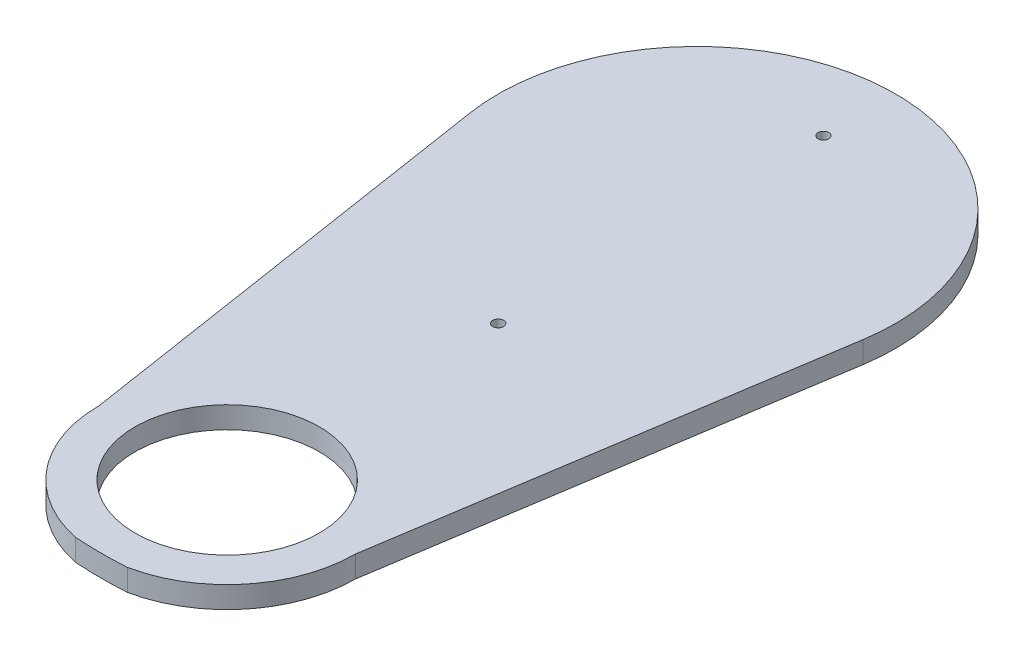
SolidWorks part; units mm, degrees
ref_plane "Front" through (0, 0, 0) normal (0, 0, 1) x (1, 0, 0)
ref_plane "Top" through (0, 0, 0) normal (0, 1, 0) x (1, 0, 0)
ref_plane "Right" through (0, 0, 0) normal (1, 0, 0) x (0, 0, -1)
sketch "Sketch1" plane through (0, 0, 0) normal (0, 1, 0) x (1, 0, 0)
  line L0 (110, 0) -> (-110, 0) construction
  line L1 (0, 0) -> (0, -110) construction
  line L2 (0, 0) -> (0, 110) construction
  line L3 (63.2456, 90) -> (-63.2456, 90)
  line L4 (80.4674, -75) -> (-80.4674, -75)
  circle A0 centre (0, 0) radius 110
  circle A1 centre (0, -75) radius 25.5
  circle A3 centre (0, 90) radius 1.5
  circle A4 centre (0, 0) radius 1.5
  point P6 (0, 0)
  point P16 (0, 90)
  point P19 (0, -75)
  dimension "D1" = 220
  dimension "D3" = 51
  dimension "D2" = 75
  dimension "D4" = 3
  dimension "D5" = 90
  dimension "D6" = 3
extrude "Boss-Extrude1" add sketch "Sketch1" along normal blind 6 contours A3 L3 A0 L4 A1 A4 | A1 L4 A0 | A3 L3 A0
sketch "Sketch2" plane through (0, 6, 0) normal (0, 1, 0) x (1, 0, 0)
  line L0 (-35.5, -75) -> (-54.3505, 46.5726)
  line L1 (0, 0) -> (50000, 0) construction
  line L2 (118.3296, 110) -> (-118.3296, 110) construction
  line L3 (0, 110) -> (0, 0) construction
  line L4 (35.5, -75) -> (54.3505, 46.5726)
  circle A3 centre (0, 55) radius 55
  circle A4 centre (0, -75) radius 25.5 construction
  circle A5 centre (0, -75) radius 25.5
  circle A6 centre (0, -75) radius 35.5
  point P9 (0, 110)
  circle M4 centre (0, 0) radius 110
  dimension "D1" = 10
extrude "Cut-Extrude1" cut sketch "Sketch2" against normal blind 10 contours A6 A3 L4 M4 | A6 L0 A3 M4
